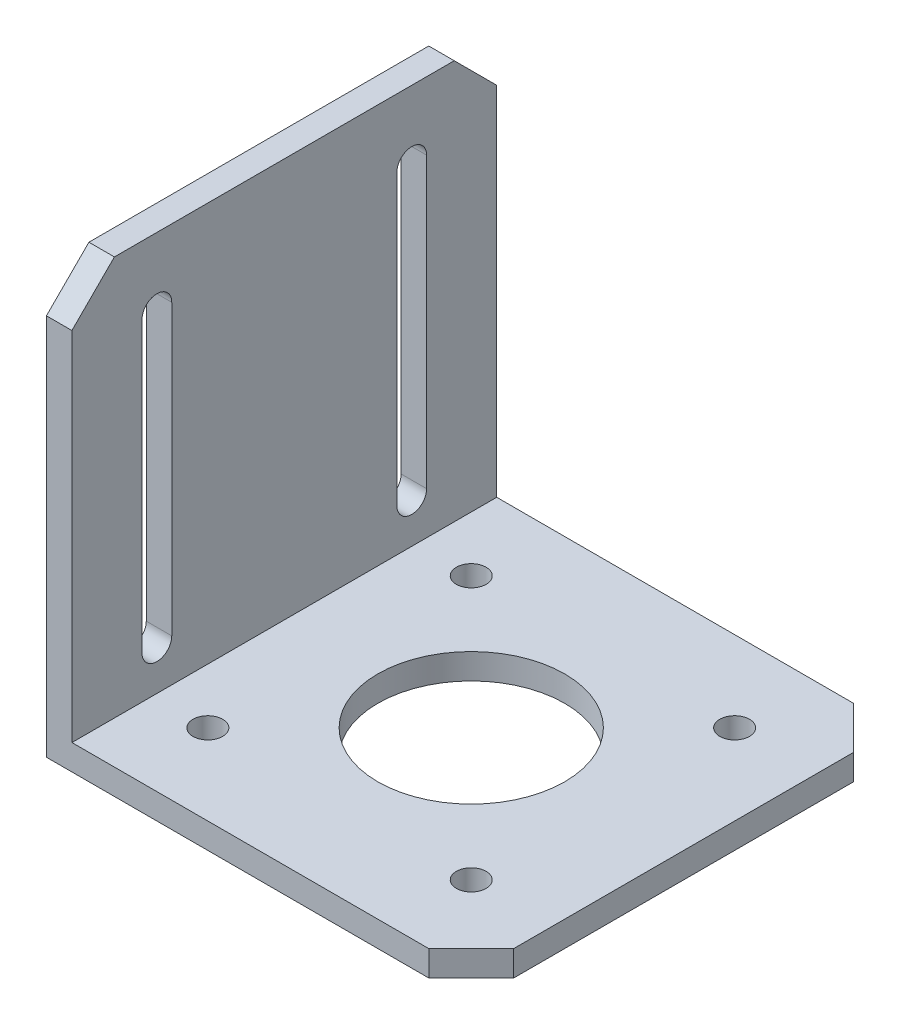
SolidWorks part; units mm, degrees
ref_plane "Front Plane" through (0, 0, 0) normal (0, 0, 1) x (1, 0, 0)
ref_plane "Top Plane" through (0, 0, 0) normal (0, 1, 0) x (1, 0, 0)
ref_plane "Right Plane" through (0, 0, 0) normal (1, 0, 0) x (0, 0, -1)
sketch "Sketch1" plane through (0, 0, 0) normal (0, 1, 0) x (1, 0, 0)
  line L1 (0, 0) -> (50, 0)
  line L2 (0, 0) -> (0, 50)
  line L3 (0, 50) -> (50, 50)
  line L4 (50, 0) -> (50, 50)
  circle A0 centre (25, 25) radius 11
  circle A1 centre (40.5, 40.5) radius 1.75
  circle A2 centre (9.5, 40.5) radius 1.75
  circle A3 centre (9.5, 9.5) radius 1.75
  circle A4 centre (40.5, 9.5) radius 1.75
  point P18 (25, 25)
  dimension "D3" = 22
  dimension "D6" = 3.5
  dimension "D1" = 50
  dimension "D2" = 50
  dimension "D4" = 25
  dimension "D5" = 25
  dimension "D7" = 9.5
  dimension "D8" = 9.5
  dimension "D9" = 4
extrude "Boss-Extrude1" add sketch "Sketch1" along normal blind 3
sketch "Sketch2" plane through (0, 3, 0) normal (0, 1, 0) x (1, 0, 0)
  line L0 (0, 0) -> (50, 0) construction
  line L1 (0, 50) -> (3, 50)
  line L2 (0, 50) -> (0, 0)
  line L3 (0, 0) -> (3, 0)
  line L4 (3, 50) -> (3, 0)
  dimension "D1" = 3
extrude "Boss-Extrude2" add sketch "Sketch2" along normal blind 47
sketch "Sketch3" plane through (0, 0, 0) normal (-1, 0, 0) x (0, 0, 1)
  line L1 (-50, 50) -> (-50, 0) construction
  line L2 (-50, 0) -> (0, 0) construction
  line L3 (0, 50) -> (0, 0) construction
  line L4 (-38.25, 42) -> (-38.25, 8)
  line L5 (-41.75, 42) -> (-41.75, 8)
  line L6 (-11.75, 42) -> (-11.75, 8)
  line L7 (-8.25, 42) -> (-8.25, 8)
  arc A0 (-38.25, 42) -> (-41.75, 42) centre (-40, 42) ccw
  arc A1 (-41.75, 8) -> (-38.25, 8) centre (-40, 8) ccw
  arc A2 (-8.25, 42) -> (-11.75, 42) centre (-10, 42) ccw
  arc A3 (-11.75, 8) -> (-8.25, 8) centre (-10, 8) ccw
  dimension "D1" = 3.5
  dimension "D2" = 3.5
  dimension "D7" = 3.5
  dimension "D8" = 3.5
  dimension "D3" = 34
  dimension "D4" = 10
  dimension "D5" = 8
  dimension "D6" = 34
  dimension "D9" = 8
  dimension "D10" = 10
extrude "Cut-Extrude1" cut sketch "Sketch3" against normal up to next
chamfer "Chamfer1" distance 5 angle 45 2 edges at (1.5, 50, 0) (1.5, 50, -50)
chamfer "Chamfer2" distance 5 angle 45 2 edges at (50, 1.5, -50) (50, 1.5, 0)
